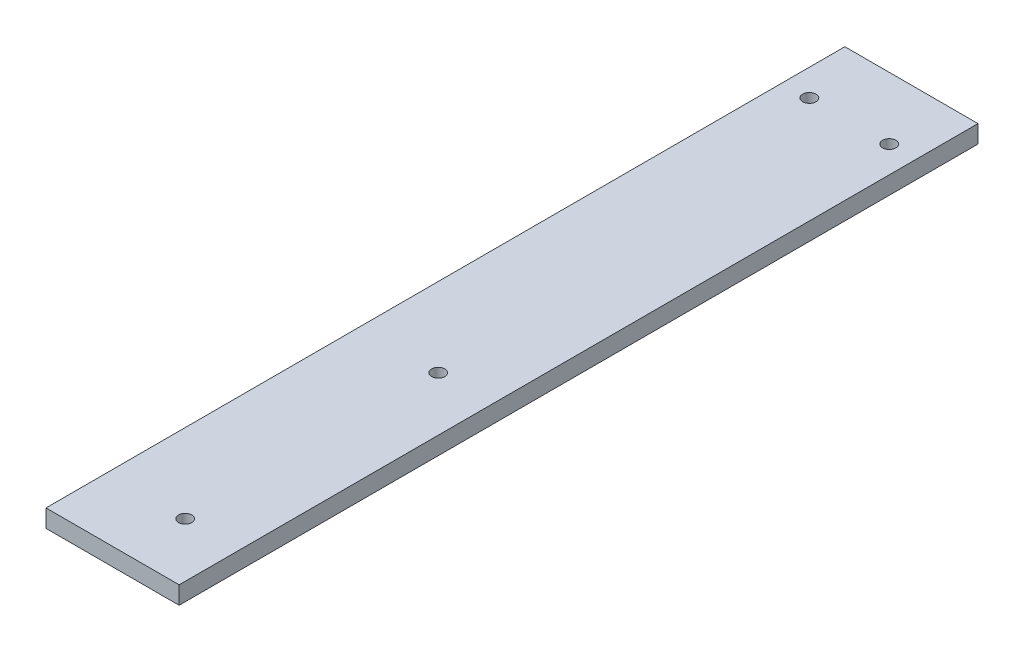
SolidWorks part; units mm, degrees
ref_plane "Front Plane" through (0, 0, 0) normal (0, 0, 1) x (1, 0, 0)
ref_plane "Top Plane" through (0, 0, 0) normal (0, 1, 0) x (1, 0, 0)
ref_plane "Right Plane" through (0, 0, 0) normal (1, 0, 0) x (0, 0, -1)
sketch "Sketch1" plane through (0, 0, 0) normal (0, 0, 1) x (1, 0, 0)
  line L1 (15, 0) -> (0, 0)
  line L2 (15, 0) -> (15, 2)
  line L3 (15, 2) -> (0, 2)
  line L4 (0, 0) -> (0, 2)
  dimension "D1" = 2
  dimension "D2" = 15
extrude "Boss-Extrude1" add sketch "Sketch1" along normal blind 90
sketch "Sketch3" plane through (0, 2, 0) normal (0, 1, 0) x (1, 0, 0)
  circle A0 centre (8.9, -83.2201) radius 0.75 construction
  circle A1 centre (8.9, -83.2201) radius 0.75
  circle A2 centre (8.9, -54.7201) radius 0.75 construction
  circle A3 centre (8.9, -54.7201) radius 0.75
  circle A4 centre (12, -7) radius 0.75 construction
  circle A5 centre (12, -7) radius 0.75
  circle A6 centre (3, -7) radius 0.75 construction
  circle A7 centre (3, -7) radius 0.75
extrude "Cut-Extrude1" cut sketch "Sketch3" against normal through all
